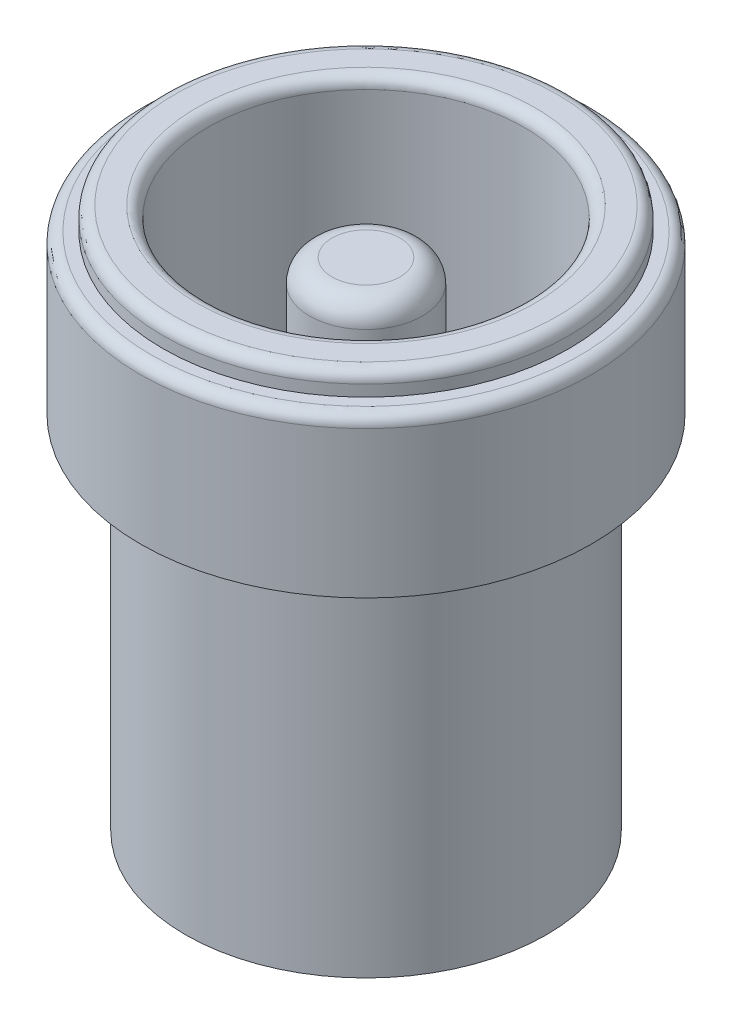
SolidWorks part; units mm, degrees
ref_plane "Front Plane" through (0, 0, 0) normal (0, 0, 1) x (1, 0, 0)
ref_plane "Top Plane" through (0, 0, 0) normal (0, 1, 0) x (1, 0, 0)
ref_plane "Right Plane" through (0, 0, 0) normal (1, 0, 0) x (0, 0, -1)
sketch "Sketch1" plane through (0, 0, 0) normal (0, 0, 1) x (1, 0, 0)
  line L0 (0, 0) -> (4.5, 0)
  line L1 (4.5, 0) -> (4.5, -0.5)
  line L2 (4.5, -0.5) -> (5, -0.5)
  line L3 (5, -0.5) -> (5, -4)
  line L4 (5, -4) -> (4, -4)
  line L5 (4, -4) -> (4, -12)
  line L6 (4, -12) -> (0, -12)
  line L7 (0, -12) -> (0, 0)
  dimension "D1" = 12
  dimension "D2" = 4
  dimension "D3" = 4
  dimension "D4" = 5
  dimension "D5" = 0.5
revolve "BULK" add sketch "Sketch1" angle 360 about L7
sketch "Sketch2" plane through (0, 0, 0) normal (0, 1, 0) x (1, 0, 0)
  circle A0 centre (0, 0) radius 3.5
  circle A1 centre (0, 0) radius 1.25
  dimension "D1" = 7
  dimension "D2" = 2.5
extrude "INSIDE CUT" cut sketch "Sketch2" against normal blind 10
sketch "Sketch3" plane through (0, 0, 0) normal (0, 1, 0) x (1, 0, 0)
  circle A1 centre (0, 0) radius 1.25
  circle A2 centre (0, 0) radius 1.25
  dimension "D1" = 0
extrude "PIN SHORTENING" cut sketch "Sketch3" against normal blind 1
fillet "Fillet1" radius 0.5 1 edges at (0, -1, 1.25)
fillet "Fillet2" radius 0.25 4 edges at (0, 0, -4.5) (0, -0.5, -5) (0, 0, 3.5) (0, -10, 3.5)
